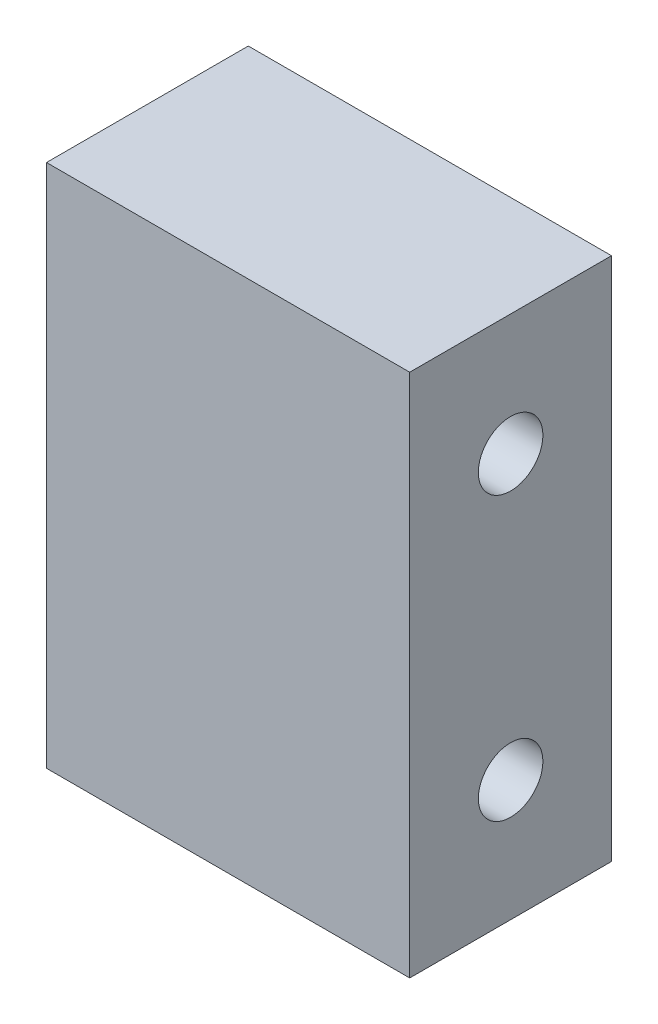
SolidWorks part; units mm, degrees
ref_plane "Front" through (0, 0, 0) normal (0, 0, 1) x (1, 0, 0)
ref_plane "Top" through (0, 0, 0) normal (0, 1, 0) x (1, 0, 0)
ref_plane "Right" through (0, 0, 0) normal (1, 0, 0) x (0, 0, -1)
sketch "Sketch1" plane through (0, 0, 0) normal (0, 0, 1) x (1, 0, 0)
  line L1 (0, 0) -> (45, 0)
  line L2 (0, 0) -> (0, 65)
  line L3 (0, 65) -> (45, 65)
  line L4 (45, 0) -> (45, 65)
  dimension "D1" = 65
  dimension "D2" = 45
extrude "Boss-Extrude1" add sketch "Sketch1" along normal blind 25
sketch "Sketch2" plane through (45, 0, 0) normal (1, 0, 0) x (0, 0, -1)
  line L0 (0, 0) -> (0, 65) construction
  line L1 (-25, 0) -> (0, 0) construction
  line L2 (-25, 65) -> (0, 65) construction
  circle A0 centre (-12.5, 50) radius 4
  circle A1 centre (-12.5, 15) radius 4
  dimension "D1" = 8
  dimension "D2" = 12.5
  dimension "D3" = 15
  dimension "D4" = 15
extrude "Cut-Extrude1" cut sketch "Sketch2" against normal blind 25
